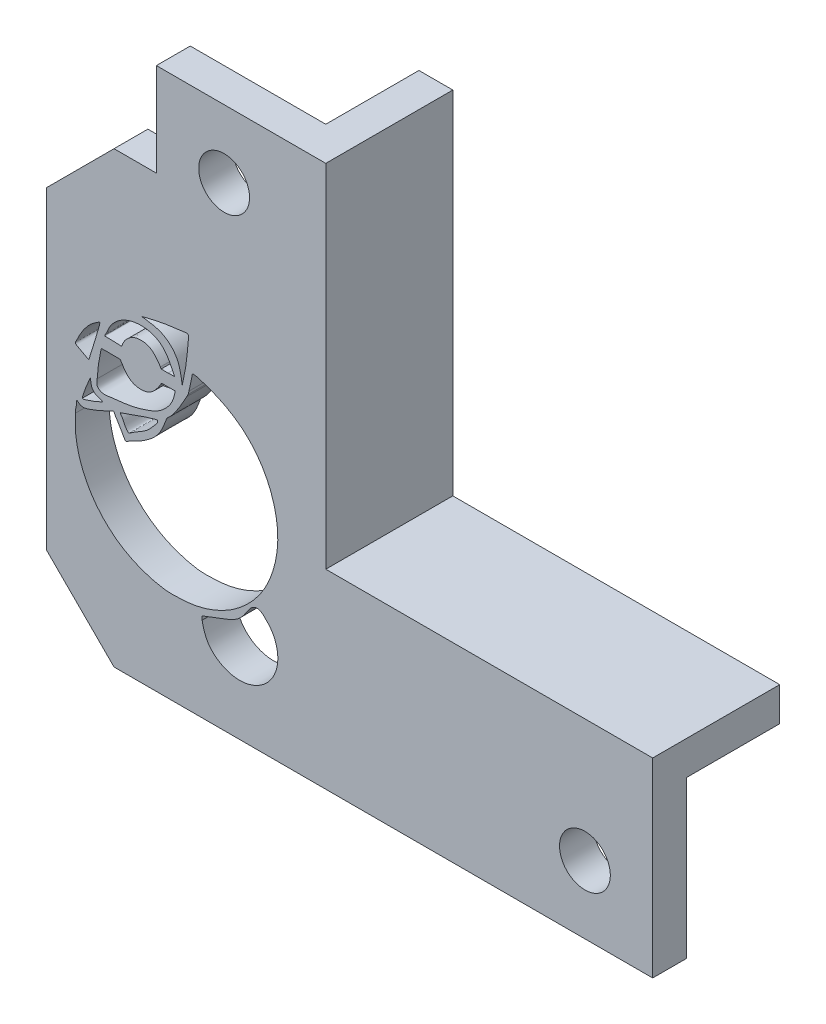
SolidWorks part; units mm, degrees
ref_plane "Alzado" through (0, 0, 0) normal (0, 0, 1) x (1, 0, 0)
ref_plane "Planta" through (0, 0, 0) normal (0, 1, 0) x (1, 0, 0)
ref_plane "Vista lateral" through (0, 0, 0) normal (1, 0, 0) x (0, 0, -1)
sketch "Croquis1" plane through (0, 0, 0) normal (0, 0, 1) x (1, 0, 0)
  line L0 (13.3781, -2.2487) -> (-7.9219, -2.2487)
  line L9 (-7.9219, -2.2487) -> (-7.9219, -24.9987)
  line L10 (-7.9219, -24.9987) -> (-15.9219, -24.9987)
  line L11 (-27.6219, -24.9987) -> (-7.9219, -24.9987) construction
  line L12 (-15.9219, -24.9987) -> (-15.9219, 7.0013)
  line L14 (-15.9219, 7.0013) -> (13.3781, 7.0013)
  line L15 (13.3781, -0.9987) -> (13.3781, 16.0013) construction
  line L16 (13.3781, 7.0013) -> (13.3781, -2.2487)
  line L17 (13.3781, 3.0013) -> (9.3781, 3.0013) construction
  line L18 (-11.9219, -24.9987) -> (-11.9219, -20.9987) construction
  line L19 (-7.9219, -0.9987) -> (13.3781, -0.9987) construction
  circle A3 centre (9.3781, 3.0013) radius 1.5
  circle A4 centre (-11.9219, -20.9987) radius 1.5
  dimension "D1" = 3
  dimension "D2" = 1.25
  dimension "D3" = 4
extrude "Saliente-Extruir1" add sketch "Croquis1" against normal blind 2
sketch "Croquis3" plane through (0, 0, 0) normal (0, 0, 1) x (1, 0, 0)
  line L0 (13.3781, -2.2487) -> (13.3781, -4.2487)
  line L1 (13.3781, -4.2487) -> (-5.9219, -4.2487)
  line L2 (-5.9219, -4.2487) -> (-5.9219, -24.9987)
  line L3 (-5.9219, -24.9987) -> (-7.9219, -24.9987)
  line L4 (-7.9219, -24.9987) -> (-7.9219, -2.2487)
  line L5 (-7.9219, -2.2487) -> (13.3781, -2.2487)
  dimension "D1" = 2
extrude "Saliente-Extruir2" add sketch "Croquis3" against normal blind 7.5
chamfer "Chaflán1" distance 4 angle 45 1 edges at (-15.9219, 7.0013, -1)
ref_plane "Plano1" through (0, -24.9987, 0) normal (0, -1, 0) x (-1, 0, 0)
mirror "Simetría1" about plane through (0, -24.9987, 0) normal (0, -1, 0) of bodies 104
sketch "Croquis4" plane through (0, 7.0013, 0) normal (0, 1, 0) x (1, 0, 0)
  line L1 (25.3551, 28.6148) -> (-27.2184, 28.6148)
  line L2 (25.3551, 28.6148) -> (25.3551, -17.6955)
  line L3 (25.3551, -17.6955) -> (-27.2184, -17.6955)
  line L4 (-27.2184, 28.6148) -> (-27.2184, -17.6955)
extrude "Cortar-Extruir1" cut sketch "Croquis4" against normal up to surface (32 mm away)
sketch "Croquis5" plane through (0, 0, 0) normal (0, 0, 1) x (1, 0, 0)
  line L0 (-22.4219, -28.9987) -> (-22.4219, -26.4987) construction
  line L1 (-11.9219, -56.9987) -> (-22.4219, -56.9987)
  line L2 (-11.9219, -56.9987) -> (-11.9219, -30.4987)
  line L3 (-11.9219, -30.4987) -> (-22.4219, -30.4987)
  line L4 (-22.4219, -56.9987) -> (-22.4219, -30.4987)
  circle A0 centre (-11.9219, -28.9987) radius 1.5 construction
  point P7 (-22.4219, -27.7487)
extrude "Saliente-Extruir3" add sketch "Croquis5" against normal up to surface (2 mm away) up to face at (-4.6933, -44.6416, -2)
chamfer "Chaflán2" distance 4 angle 45 2 edges at (-22.4219, -56.9987, -1) (-22.4219, -30.4987, -1)
sketch "Croquis8" plane through (0, 0, 0) normal (0, 0, 1) x (1, 0, 0)
  line L0 (-14.1296, -41.0327) -> (-14.0447, -40.8722)
  line L1 (-14.0447, -40.8722) -> (-13.9984, -40.681)
  line L2 (-16.0263, -51.402) -> (-15.9885, -51.4054)
  line L3 (-19.8022, -43.0269) -> (-19.8071, -42.8981)
  line L4 (-19.8071, -42.8981) -> (-19.8415, -42.9664)
  line L5 (-18.612, -41.0839) -> (-18.0529, -41.0862)
  line L6 (-15.65, -41.1576) -> (-15.6248, -41.0862)
  line L7 (-15.6248, -41.0862) -> (-15.216, -41.0839)
  line L8 (-15.216, -41.0839) -> (-14.8071, -41.0816)
  line L9 (-14.8071, -41.0816) -> (-14.8131, -41.1349)
  line L10 (-19.376, -43.1473) -> (-19.376, -43.1475)
  line L11 (-15.2341, -40.375) -> (-15.6408, -40.3727)
  line L12 (-15.6408, -40.3727) -> (-15.6829, -40.2821)
  line L13 (-15.2341, -40.375) -> (-14.8521, -40.3593)
  line L14 (-14.8521, -40.3593) -> (-14.8581, -40.3258)
  line L15 (-14.4072, -40.4879) -> (-14.4064, -40.6046)
  line L16 (-14.4064, -40.6046) -> (-14.3852, -40.5243)
  line L17 (-13.1137, -51.7417) -> (-13.2206, -51.7818)
  line L18 (-13.2206, -51.7818) -> (-13.2206, -52.0041)
  spline S0 degree 3 poles (-20.6937, -41.5211) (-20.6395, -41.422) (-20.5612, -41.2438) (-20.4324, -40.9984) (-20.2964, -40.7651) (-20.1484, -40.5504) (-19.9966, -40.3594) (-19.8471, -40.1993) (-19.6957, -40.0685) (-19.5308, -39.952) (-19.4025, -39.8673) (-19.3156, -39.8128) (-19.2919, -39.7985) (-19.2643, -39.7952) (-19.2586, -39.8211) (-19.2614, -39.8463) (-19.2707, -39.904) (-19.2881, -39.9809) (-19.3159, -40.0743) (-19.3529, -40.1835) (-19.3937, -40.3204) (-19.44, -40.4873) (-19.4855, -40.653) (-19.532, -40.8128) (-19.5782, -40.9656) (-19.6264, -41.1212) (-19.6763, -41.2808) (-19.7277, -41.4444) (-19.7678, -41.5716) (-19.7964, -41.6621) (-19.8134, -41.7164) (-19.8292, -41.7674) (-19.8437, -41.815) (-19.8567, -41.8587) (-19.8674, -41.8953) (-19.876, -41.9249) (-19.8824, -41.9486) (-19.8878, -41.971) (-19.8922, -41.9915) (-19.8971, -42.0079) (-19.9064, -42.0269) (-19.9384, -42.0292) (-19.9705, -42.0094) (-20.0323, -41.9699) (-20.115, -41.9192) (-20.2182, -41.868) (-20.3146, -41.8233) (-20.4104, -41.7739) (-20.5123, -41.7177) (-20.5956, -41.6704) (-20.6574, -41.6349) (-20.6899, -41.6114) (-20.7095, -41.5809) (-20.7056, -41.5492) (-20.6937, -41.5211) (-20.6395, -41.422) (-20.5612, -41.2438) knots -0.016381 -0.011609 -0.006068 0 0.048923 0.098274 0.148594 0.193744 0.238041 0.279376 0.311074 0.345219 0.387458 0.394118 0.399629 0.403043 0.406341 0.41143 0.417393 0.437276 0.453958 0.469591 0.499137 0.530572 0.562489 0.591376 0.61982 0.648164 0.678785 0.709513 0.740174 0.750309 0.760466 0.770692 0.778953 0.787156 0.795171 0.799387 0.803705 0.808322 0.811747 0.814958 0.817604 0.822431 0.829505 0.837912 0.861751 0.8815 0.899704 0.918724 0.939319 0.962106 0.970183 0.977504 0.983619 0.988391 0.993932 1 1.048923 1.098274 1.148594 only from (-20.6779, -41.4921) to (-20.6779, -41.4921)
  spline S1 degree 3 poles (-20.705, -45.1671) (-20.703, -45.1333) (-20.6992, -45.0667) (-20.6907, -44.9694) (-20.6774, -44.8783) (-20.6554, -44.7926) (-20.6366, -44.7014) (-20.6355, -44.6157) (-20.6399, -44.5443) (-20.6442, -44.4941) (-20.6185, -44.4682) (-20.6043, -44.4681) (-20.6007, -44.4683) (-20.5959, -44.4693) (-20.5899, -44.4718) (-20.5834, -44.4765) (-20.5763, -44.4826) (-20.5681, -44.4897) (-20.5589, -44.4975) (-20.5408, -44.5125) (-20.5134, -44.534) (-20.4751, -44.5602) (-20.4347, -44.5831) (-20.392, -44.6014) (-20.3476, -44.615) (-20.302, -44.6239) (-20.2558, -44.6281) (-20.2094, -44.6281) (-20.1359, -44.6226) (-20.0362, -44.6028) (-19.9133, -44.5633) (-19.7721, -44.5094) (-19.6103, -44.4488) (-19.429, -44.3793) (-19.2456, -44.3039) (-19.0616, -44.2195) (-18.8759, -44.1309) (-18.7341, -44.065) (-18.6357, -44.0221) (-18.5819, -43.9966) (-18.5394, -43.9727) (-18.5083, -43.9523) (-18.4861, -43.9407) (-18.4672, -43.9371) (-18.4546, -43.9384) (-18.4477, -43.9399) (-18.4335, -43.9449) (-18.4148, -43.9623) (-18.4013, -43.9937) (-18.3856, -44.0427) (-18.3571, -44.1035) (-18.3128, -44.1709) (-18.2607, -44.2429) (-18.2078, -44.327) (-18.1531, -44.4229) (-18.0997, -44.5203) (-18.0453, -44.6171) (-17.9899, -44.712) (-17.9383, -44.7958) (-17.8903, -44.8693) (-17.8484, -44.9366) (-17.8178, -44.9941) (-17.7971, -45.0397) (-17.7824, -45.0674) (-17.7567, -45.1016) (-17.6887, -45.1047) (-17.618, -45.0622) (-17.5156, -44.9954) (-17.3884, -44.9222) (-17.2384, -44.855) (-17.0969, -44.7933) (-16.9599, -44.7209) (-16.8236, -44.6405) (-16.6575, -44.5356) (-16.4647, -44.408) (-16.2522, -44.2496) (-16.0642, -44.0831) (-15.9027, -43.9075) (-15.7655, -43.7277) (-15.6362, -43.5206) (-15.5229, -43.2843) (-15.4203, -43.0236) (-15.3541, -42.8443) (-15.3172, -42.7492) (-15.3123, -42.7378) (-15.3065, -42.7266) (-15.2992, -42.716) (-15.2907, -42.7058) (-15.2801, -42.6946) (-15.2674, -42.6825) (-15.2526, -42.6696) (-15.2024, -42.6267) (-15.121, -42.5488) (-15.0148, -42.4301) (-14.9021, -42.2893) (-14.7827, -42.1273) (-14.6583, -41.9436) (-14.5302, -41.7404) (-14.3987, -41.5176) (-14.2629, -41.2759) (-14.1741, -41.1138) (-14.1296, -41.0327) knots 0 0 0 0 0.010102 0.019921 0.029199 0.037535 0.046355 0.056958 0.06293 0.067937 0.071476 0.071821 0.072175 0.072528 0.073305 0.074093 0.074894 0.076117 0.077323 0.078522 0.083117 0.087739 0.092362 0.096977 0.101593 0.106206 0.110819 0.115434 0.120044 0.132827 0.145679 0.15859 0.177979 0.197286 0.216612 0.237194 0.257754 0.27809 0.283919 0.28981 0.295884 0.298456 0.300941 0.303334 0.304032 0.304734 0.305424 0.30853 0.31193 0.31556 0.323929 0.331848 0.339652 0.350489 0.361504 0.372618 0.383692 0.394667 0.405445 0.413097 0.420888 0.429133 0.432554 0.435786 0.438589 0.444871 0.453411 0.463207 0.481417 0.497174 0.512277 0.527524 0.543418 0.55955 0.586221 0.6125 0.638665 0.661117 0.683659 0.70615 0.733949 0.761816 0.789817 0.791057 0.79229 0.793517 0.794828 0.796146 0.797469 0.79943 0.801385 0.803339 0.819145 0.835 0.850886 0.873014 0.895102 0.917178 0.944771 0.972379 1 1 1 1
  spline S2 degree 3 poles (-13.9984, -40.681) (-13.9903, -40.6468) (-13.9742, -40.5783) (-13.9503, -40.4751) (-13.9272, -40.37) (-13.9053, -40.2633) (-13.8838, -40.1563) (-13.8633, -40.0581) (-13.8427, -39.9682) (-13.8254, -39.8826) (-13.8159, -39.8118) (-13.8115, -39.7582) (-13.8059, -39.7265) (-13.7911, -39.6987) (-13.7618, -39.6867) (-13.7292, -39.6851) (-13.675, -39.6891) (-13.6041, -39.6989) (-13.519, -39.7177) (-13.1718, -39.8137) (-12.5569, -40.022) (-11.7059, -40.4223) (-10.9145, -40.9398) (-10.2352, -41.5837) (-9.6804, -42.3223) (-9.245, -43.1444) (-8.9354, -44.0298) (-8.7622, -44.9576) (-8.7405, -45.7358) (-8.7986, -46.3433) (-8.8745, -46.7832) (-8.9814, -47.216) (-9.1169, -47.6401) (-9.282, -48.053) (-9.4748, -48.4458) (-9.6941, -48.8162) (-9.9365, -49.1635) (-10.1729, -49.4545) (-10.3935, -49.6949) (-10.5903, -49.8911) (-10.7885, -50.0727) (-10.9864, -50.2408) (-11.1837, -50.3953) (-11.3885, -50.5412) (-11.601, -50.6773) (-11.8204, -50.8041) (-12.039, -50.9189) (-12.2558, -51.0232) (-12.4703, -51.1171) (-12.6866, -51.2019) (-12.9046, -51.277) (-13.1239, -51.3428) (-13.3467, -51.4002) (-13.5729, -51.4491) (-13.802, -51.4891) (-14.0115, -51.5166) (-14.2005, -51.5344) (-14.3686, -51.5459) (-14.541, -51.554) (-14.7177, -51.5594) (-14.8987, -51.5619) (-15.0629, -51.5614) (-15.2101, -51.5587) (-15.3402, -51.5523) (-15.4505, -51.5411) (-15.5409, -51.5268) (-15.612, -51.5136) (-15.6847, -51.4993) (-15.759, -51.4846) (-15.8351, -51.4695) (-15.9017, -51.4559) (-15.9589, -51.4438) (-16.0065, -51.4329) (-16.0433, -51.4234) (-16.0695, -51.4159) (-16.0852, -51.4114) (-16.1036, -51.406) (-16.1248, -51.4001) (-16.1489, -51.3936) (-16.174, -51.3869) (-16.2001, -51.3801) (-16.2273, -51.373) (-16.4624, -51.3111) (-16.8996, -51.1685) (-17.5153, -50.89) (-18.0956, -50.5452) (-18.6312, -50.1372) (-19.1161, -49.6727) (-19.547, -49.1547) (-19.9171, -48.5889) (-20.2231, -47.9843) (-20.3977, -47.5202) (-20.4887, -47.2205) (-20.5243, -47.0932) (-20.5571, -46.9646) (-20.5871, -46.8346) (-20.6139, -46.7032) (-20.6387, -46.5626) (-20.6608, -46.4128) (-20.6788, -46.2538) (-20.6981, -46.1197) (-20.7007, -46.0093) (-20.7044, -45.9239) (-20.7075, -45.8231) (-20.7099, -45.7067) (-20.711, -45.5749) (-20.7104, -45.4564) (-20.7089, -45.3511) (-20.7071, -45.2591) (-20.7057, -45.1977) (-20.705, -45.1671) knots 0 0 0 0 0.003682 0.007375 0.011092 0.01495 0.018784 0.02253 0.025452 0.028444 0.031678 0.032922 0.034074 0.035059 0.036052 0.037215 0.038477 0.041726 0.044715 0.047594 0.079453 0.112577 0.145859 0.178045 0.210101 0.242202 0.275109 0.307972 0.340688 0.356264 0.371832 0.387406 0.402922 0.418432 0.433936 0.448708 0.463482 0.478249 0.487949 0.497647 0.507348 0.516096 0.524842 0.533584 0.542422 0.551265 0.560111 0.568287 0.576459 0.584629 0.592616 0.600606 0.608597 0.616717 0.624836 0.632953 0.638836 0.644719 0.650602 0.656918 0.663234 0.669558 0.67411 0.678657 0.683198 0.685719 0.688243 0.690768 0.693476 0.696183 0.69889 0.700597 0.702303 0.704009 0.70458 0.705151 0.705721 0.706591 0.70746 0.70833 0.70931 0.71029 0.711271 0.734773 0.758343 0.781923 0.805322 0.828713 0.852108 0.875744 0.899374 0.922951 0.927566 0.932179 0.936792 0.941472 0.946153 0.950833 0.956421 0.962011 0.967602 0.970586 0.97357 0.976554 0.981156 0.985757 0.990359 0.993573 0.996786 1 1 1 1
  spline S3 degree 3 poles (-20.2849, -44.1798) (-20.2813, -44.1838) (-20.2744, -44.1916) (-20.2633, -44.2023) (-20.2483, -44.2121) (-20.2266, -44.2153) (-20.2015, -44.2112) (-20.1676, -44.2016) (-20.1259, -44.1895) (-20.0772, -44.175) (-20.0108, -44.1543) (-19.9256, -44.1257) (-19.8213, -44.0885) (-19.7165, -44.0494) (-19.6119, -44.0093) (-19.5077, -43.968) (-19.4041, -43.9252) (-19.3011, -43.8806) (-19.1982, -43.8347) (-19.1298, -43.8037) (-19.0955, -43.7882) knots 0 0 0 0 0.012524 0.024539 0.035838 0.054146 0.074153 0.09522 0.13656 0.175806 0.214299 0.299502 0.386353 0.473661 0.561511 0.6489 0.736148 0.823979 0.911952 1 1 1 1
  spline S4 degree 3 poles (-19.0955, -43.7882) (-19.1351, -43.7508) (-19.2074, -43.6824) (-19.3521, -43.676) (-19.4674, -43.6279) (-19.5675, -43.5642) (-19.6489, -43.4859) (-19.7163, -43.3901) (-19.7608, -43.277) (-19.7864, -43.1533) (-19.7969, -43.0692) (-19.8022, -43.0269) knots 0 0 0 0 0.138927 0.254224 0.368506 0.467541 0.567312 0.665829 0.775568 0.886827 1 1 1 1
  spline S5 degree 3 poles (-19.8415, -42.9664) (-19.8574, -43.0003) (-19.8893, -43.0681) (-19.9364, -43.1701) (-19.9843, -43.2779) (-20.0317, -43.3919) (-20.0791, -43.5123) (-20.1247, -43.633) (-20.1692, -43.7534) (-20.2114, -43.8736) (-20.2412, -43.9665) (-20.2604, -44.0317) (-20.2716, -44.0691) (-20.2814, -44.0995) (-20.2895, -44.1226) (-20.2935, -44.1385) (-20.294, -44.1524) (-20.2914, -44.1632) (-20.2884, -44.1715) (-20.286, -44.177) (-20.2849, -44.1798) knots 0 0 0 0 0.086456 0.172862 0.259182 0.358492 0.457904 0.557618 0.656119 0.754324 0.85152 0.881143 0.911068 0.941758 0.954766 0.967438 0.979627 0.986268 0.993075 1 1 1 1
  spline S6 degree 3 poles (-19.4152, -42.7587) (-19.4114, -42.7031) (-19.4036, -42.592) (-19.3907, -42.4253) (-19.3753, -42.2581) (-19.3562, -42.0907) (-19.3332, -41.9232) (-19.3068, -41.7574) (-19.2769, -41.5932) (-19.2446, -41.43) (-19.2201, -41.3112) (-19.2046, -41.2365) (-19.1981, -41.2067) (-19.1917, -41.18) (-19.1853, -41.1563) (-19.1801, -41.1347) (-19.177, -41.1168) (-19.1757, -41.1028) (-19.1743, -41.094) (-19.1706, -41.0815) (-19.1509, -41.0727) (-19.1245, -41.0778) (-19.0807, -41.0875) (-19.0234, -41.0946) (-18.956, -41.0906) (-18.8844, -41.0815) (-18.8021, -41.0782) (-18.7082, -41.0798) (-18.6443, -41.0825) (-18.612, -41.0839) knots 0 0 0 0 0.074067 0.148144 0.222254 0.297231 0.372177 0.44698 0.520436 0.594028 0.66812 0.681788 0.695364 0.708732 0.718295 0.728004 0.738207 0.742505 0.746592 0.750185 0.759181 0.771453 0.785688 0.819015 0.84772 0.8751 0.915063 0.95701 1 1 1 1
  spline S7 degree 3 poles (-18.0529, -41.0862) (-17.9813, -41.2114) (-17.8523, -41.4369) (-17.6122, -41.7235) (-17.3353, -41.9265) (-17.007, -42.0166) (-16.6722, -42.0167) (-16.344, -41.9267) (-16.066, -41.7246) (-15.8444, -41.4547) (-15.7155, -41.2578) (-15.65, -41.1576) knots 0 0 0 0 0.136926 0.246871 0.353654 0.457939 0.564976 0.66927 0.77609 0.886062 1 1 1 1
  spline S8 degree 3 poles (-14.8131, -41.1349) (-14.8268, -41.1941) (-14.8542, -41.3124) (-14.902, -41.4876) (-14.9651, -41.6623) (-15.0515, -41.8318) (-15.1588, -41.995) (-15.2811, -42.148) (-15.4151, -42.2911) (-15.5603, -42.4222) (-15.7398, -42.557) (-15.9599, -42.6844) (-16.2194, -42.8002) (-16.5095, -42.9065) (-16.8262, -43.0089) (-17.1695, -43.1009) (-17.5249, -43.1743) (-17.8928, -43.2239) (-18.2726, -43.2637) (-18.5858, -43.3007) (-18.8299, -43.3391) (-19.0074, -43.3499) (-19.1552, -43.3236) (-19.2639, -43.2741) (-19.3372, -43.2235) (-19.4052, -43.1483) (-19.4404, -43.0345) (-19.4363, -42.8988) (-19.4224, -42.8065) (-19.4152, -42.7587) knots 0 0 0 0 0.030514 0.060875 0.091074 0.123479 0.156092 0.188835 0.221644 0.254321 0.286863 0.334053 0.381524 0.429239 0.488965 0.54839 0.607474 0.670827 0.734521 0.799048 0.828969 0.858453 0.887903 0.9031 0.918089 0.932304 0.953175 0.975771 1 1 1 1
  spline S9 degree 3 poles (-15.6829, -40.2821) (-15.7423, -40.1948) (-15.8643, -40.0153) (-16.0765, -39.7668) (-16.3476, -39.5736) (-16.6682, -39.4875) (-16.9965, -39.4893) (-17.3197, -39.5768) (-17.5909, -39.7729) (-17.8405, -40.0298) (-17.9285, -40.2583) (-17.9755, -40.3803) knots 0 0 0 0 0.105184 0.21629 0.324229 0.431264 0.541221 0.64875 0.758595 0.871181 1 1 1 1
  spline S10 degree 3 poles (-14.8581, -40.3258) (-14.9351, -40.1627) (-15.0861, -39.8426) (-15.3542, -39.3949) (-15.714, -39.026) (-16.1826, -38.8076) (-16.6984, -38.7205) (-17.2374, -38.7511) (-17.7627, -38.9068) (-18.2372, -39.192) (-18.5139, -39.4858) (-18.6523, -39.6933) (-18.702, -39.7777) (-18.7453, -39.8636) (-18.7804, -39.9545) (-18.8204, -40.0554) (-18.8725, -40.1491) (-18.9215, -40.2331) (-18.9644, -40.2912) (-18.9509, -40.3463) (-18.9276, -40.3517) (-18.9153, -40.3537) (-18.891, -40.356) (-18.8562, -40.3581) (-18.8112, -40.3587) (-18.7525, -40.3582) (-18.6787, -40.3582) (-18.4147, -40.359) (-18.1802, -40.3704) (-17.9755, -40.3803) knots 0 0 0 0 0.082563 0.161975 0.238037 0.314442 0.394253 0.475384 0.559532 0.642495 0.726015 0.741509 0.756605 0.770808 0.785501 0.801158 0.820459 0.834373 0.845936 0.852823 0.854559 0.856517 0.858572 0.865705 0.872491 0.879156 0.89258 0.906246 1 1 1 1
  spline S11 degree 3 poles (-18.0436, -43.8078) (-18.0427, -43.7988) (-18.0364, -43.7984) (-18.0324, -43.7972) (-18.0276, -43.7962) (-18.0223, -43.795) (-18.0164, -43.7938) (-18.0103, -43.7927) (-18.0041, -43.7916) (-17.9978, -43.7905) (-17.9882, -43.7887) (-17.9755, -43.7855) (-17.9598, -43.7807) (-17.9393, -43.7737) (-17.9138, -43.7651) (-17.8833, -43.7548) (-17.8501, -43.7435) (-17.8143, -43.7309) (-17.7758, -43.7171) (-17.6387, -43.6673) (-17.4033, -43.5825) (-17.0737, -43.4654) (-16.7879, -43.3659) (-16.5428, -43.2826) (-16.3231, -43.2115) (-16.1419, -43.1568) (-16.0004, -43.115) (-15.9282, -43.0998) (-15.8326, -43.086) (-15.8474, -43.2523) (-15.9722, -43.3693) (-16.1275, -43.5753) (-16.3068, -43.7662) (-16.4915, -43.9389) (-16.6867, -44.0785) (-16.9086, -44.2057) (-17.1594, -44.3479) (-17.3438, -44.47) (-17.4579, -44.5566) (-17.5038, -44.5847) (-17.5516, -44.5938) (-17.5908, -44.576) (-17.6219, -44.55) (-17.6693, -44.4987) (-17.7259, -44.422) (-17.783, -44.3181) (-17.8295, -44.2168) (-17.8745, -44.1189) (-17.926, -44.0238) (-17.9782, -43.9509) (-18.0227, -43.8994) (-18.0474, -43.864) (-18.0523, -43.8329) (-18.0473, -43.8149) (-18.0436, -43.8078) (-18.0427, -43.7988) (-18.0364, -43.7984) knots -0.004561 -0.003086 -0.001558 0 0.000765 0.001529 0.002294 0.003371 0.004447 0.005525 0.006682 0.007839 0.008995 0.011926 0.014862 0.017804 0.023568 0.029324 0.035074 0.042398 0.049729 0.05708 0.120698 0.18415 0.245016 0.28328 0.323249 0.368804 0.385867 0.401006 0.41154 0.428157 0.465111 0.509875 0.563703 0.606517 0.645333 0.692328 0.743801 0.800242 0.810955 0.820709 0.829124 0.835681 0.843058 0.850892 0.873109 0.894095 0.914481 0.932953 0.951976 0.972526 0.980901 0.988609 0.995439 0.996914 0.998442 1 1.000765 1.001529 1.002294 only from (-18.0406, -43.7992) to (-18.0406, -43.7992)
  spline S12 degree 3 poles (-16.677, -38.2734) (-16.5452, -38.291) (-16.2832, -38.326) (-15.8964, -38.4063) (-15.5298, -38.5433) (-15.2042, -38.7563) (-14.9282, -39.0256) (-14.7072, -39.3461) (-14.5607, -39.7096) (-14.4701, -40.095) (-14.4283, -40.3564) (-14.4072, -40.4879) knots 0 0 0 0 0.113372 0.225307 0.336246 0.444835 0.554499 0.663116 0.77429 0.886434 1 1 1 1
  spline S13 degree 3 poles (-14.3852, -40.5243) (-14.3683, -40.4472) (-14.3344, -40.2929) (-14.2852, -40.0609) (-14.2351, -39.8086) (-14.1871, -39.5356) (-14.1441, -39.2424) (-14.1106, -38.9445) (-14.0886, -38.6414) (-14.0655, -38.3311) (-14.0386, -38.1053) (-14.0152, -37.9651) (-14.012, -37.9104) (-14.0214, -37.8647) (-14.039, -37.8314) (-14.0571, -37.8087) (-14.0837, -37.7878) (-14.1225, -37.778) (-14.1682, -37.7813) (-14.2967, -37.8054) (-14.5041, -37.8364) (-14.7886, -37.867) (-15.0677, -37.8974) (-15.3467, -37.9403) (-15.6275, -37.992) (-15.8992, -38.0475) (-16.1606, -38.1033) (-16.4111, -38.1612) (-16.5862, -38.2065) (-16.6872, -38.2347) (-16.7151, -38.2424) (-16.7404, -38.2491) (-16.7634, -38.2548) (-16.7837, -38.26) (-16.8001, -38.2646) (-16.8123, -38.2685) (-16.8206, -38.2708) (-16.8266, -38.2718) (-16.83, -38.2721) (-16.8308, -38.2722) (-16.8316, -38.2723) (-16.8324, -38.2725) (-16.833, -38.2728) (-16.8335, -38.2731) (-16.8338, -38.2735) (-16.8341, -38.2739) (-16.8348, -38.2754) (-16.831, -38.2801) (-16.8227, -38.2763) (-16.8086, -38.2746) (-16.791, -38.2713) (-16.7721, -38.2725) (-16.7534, -38.2754) (-16.7313, -38.276) (-16.7049, -38.2751) (-16.6865, -38.274) (-16.677, -38.2734) knots 0 0 0 0 0.041212 0.082455 0.123766 0.17547 0.227094 0.278397 0.331897 0.385715 0.44079 0.450477 0.459921 0.469239 0.474356 0.47945 0.484331 0.491741 0.499679 0.508079 0.559981 0.609076 0.65742 0.70651 0.756366 0.80641 0.851239 0.8959 0.940581 0.945615 0.950644 0.955664 0.959312 0.962967 0.966646 0.968163 0.969669 0.971157 0.971306 0.971455 0.971607 0.971727 0.971845 0.97196 0.972038 0.972116 0.972192 0.972887 0.974376 0.97633 0.980513 0.983537 0.986209 0.990375 0.995055 1 1 1 1
  spline S14 degree 3 poles (-13.1137, -51.7417) (-12.9807, -51.6919) (-12.7151, -51.5923) (-12.3177, -51.4421) (-11.9222, -51.2899) (-11.5284, -51.1341) (-11.1475, -50.9266) (-10.815, -50.6199) (-10.5677, -50.2423) (-10.3354, -49.8897) (-10.0458, -49.7549) (-9.8892, -49.7838) (-9.8332, -49.8001) (-9.7587, -49.8307) (-9.6714, -49.8843) (-9.5775, -49.9644) (-9.4866, -50.0549) (-9.3926, -50.1493) (-9.2981, -50.2499) (-9.1235, -50.4557) (-8.917, -50.8103) (-8.7644, -51.3339) (-8.7361, -51.8728) (-8.8352, -52.3922) (-9.0442, -52.8657) (-9.3604, -53.2875) (-9.7772, -53.6274) (-10.268, -53.8664) (-10.755, -53.9757) (-11.204, -53.975) (-11.6009, -53.9017) (-11.9784, -53.7613) (-12.326, -53.5615) (-12.6304, -53.3084) (-12.879, -53.0032) (-13.0491, -52.6494) (-13.1558, -52.3126) (-13.2017, -52.094) (-13.2206, -52.0041) knots 0 0 0 0 0.032722 0.065374 0.097888 0.130362 0.162947 0.197268 0.233243 0.266705 0.29431 0.298678 0.303195 0.307747 0.317199 0.326637 0.336125 0.346757 0.357339 0.367905 0.408927 0.450666 0.492527 0.532054 0.571429 0.610782 0.652424 0.694129 0.735518 0.766245 0.797021 0.828024 0.858615 0.888973 0.918776 0.948546 0.978828 1 1 1 1
extrude "Cortar-Extruir2" cut sketch "Croquis8" against normal up to next
